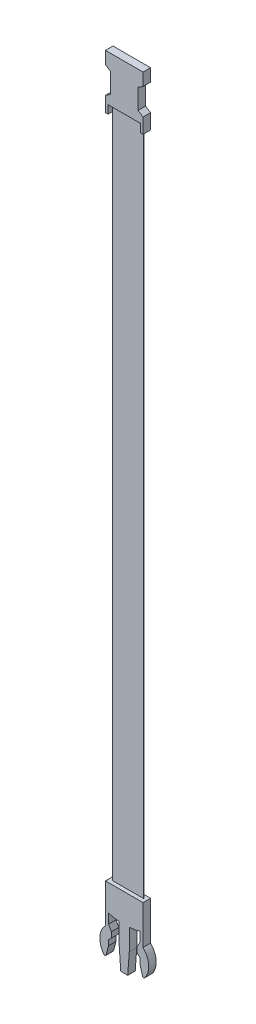
SolidWorks part; units mm, degrees
ref_plane "Plan de face" through (0, 0, 0) normal (0, 0, 1) x (1, 0, 0)
ref_plane "Plan de dessus" through (0, 0, 0) normal (0, 1, 0) x (1, 0, 0)
ref_plane "Plan de droite" through (0, 0, 0) normal (1, 0, 0) x (0, 0, -1)
sketch "Esquisse1" plane through (0, 0, 0) normal (0, 0, 1) x (1, 0, 0)
  line L1 (0, 0) -> (25, 0)
  line L2 (0, 0) -> (0, 550)
  line L3 (0, 550) -> (25, 550)
  line L4 (25, 0) -> (25, 550)
  dimension "D1" = 25
  dimension "D2" = 550
extrude "Extrusion1" add sketch "Esquisse1" along normal blind 0.2
sketch "Esquisse2" plane through (0, 0, 0.2) normal (0, 0, 1) x (1, 0, 0)
  line L0 (-2.5, 545.8754) -> (-2.5, 557.8754)
  line L1 (25, 550) -> (0, 550) construction
  line L2 (12.5, 550) -> (12.5, 576.3626) construction
  line L3 (-0.4001, 545.8754) -> (-0.4001, 552.4561)
  line L4 (-0.4001, 545.8754) -> (-2.5, 545.8754)
  line L5 (1.5, 576.4047) -> (1.5, 560.4047)
  line L6 (-2.5, 557.8754) -> (1.5, 560.4047)
  line L7 (27.5, 578.9341) -> (27.5, 588.9341)
  line L8 (-2.5, 578.9341) -> (1.5, 576.4047)
  line L9 (-2.5, 578.9341) -> (-2.5, 588.9341)
  line L10 (-2.5, 588.9341) -> (27.5, 588.9341)
  line L11 (-0.4001, 552.4561) -> (25.4001, 552.4561)
  line L12 (27.5, 578.9341) -> (23.5, 576.4047)
  line L13 (27.5, 557.8754) -> (23.5, 560.4047)
  line L14 (23.5, 576.4047) -> (23.5, 560.4047)
  line L15 (25.4001, 545.8754) -> (27.5, 545.8754)
  line L16 (25.4001, 545.8754) -> (25.4001, 552.4561)
  line L17 (27.5, 545.8754) -> (27.5, 557.8754)
  point P2 (12.5, 550)
  point P9 (12.5, 552.4561)
  point P13 (12.5, 588.9341)
  dimension "D1" = 15
  dimension "D2" = 11
extrude "Extrusion2" add sketch "Esquisse2" along normal blind 3 and the other way blind 3
sketch "Esquisse3" plane through (0, 0, 0.2) normal (0, 0, 1) x (1, 0, 0)
  line L0 (12.5, 0) -> (12.5, -25.1606) construction
  line L1 (-2.5, 15) -> (-2.5, -16.0505)
  line L2 (0, -5.9495) -> (0, -13.6431)
  line L3 (-2.5, 15) -> (27.5, 15)
  line L4 (0, 0) -> (25, 0) construction
  line L5 (0, -13.6431) -> (2.232, -17.8488)
  line L6 (2.232, -17.8488) -> (2.232, -22.1747)
  line L7 (2.232, -22.1747) -> (0, -24.4067)
  line L8 (0, -24.4067) -> (0, -28.5434)
  line L9 (0, -28.5434) -> (-2.0163, -36.0229)
  line L10 (25, -28.5434) -> (27.0163, -36.0229)
  line L11 (25, -24.4067) -> (25, -28.5434)
  line L12 (22.768, -22.1747) -> (25, -24.4067)
  line L13 (22.768, -17.8488) -> (22.768, -22.1747)
  line L14 (25, -13.6431) -> (22.768, -17.8488)
  line L15 (25, -5.9495) -> (25, -13.6431)
  line L16 (27.5, 15) -> (27.5, -16.0505)
  line L17 (8.5, -7.4942) -> (8.5, -24.4535)
  line L18 (16.5, -7.4942) -> (16.5, -24.4535)
  line L19 (9.7308, -41.4128) -> (15.2692, -41.4128)
  line L20 (9.7308, -41.4128) -> (8.5, -24.4535)
  line L21 (15.2692, -41.4128) -> (16.5, -24.4535)
  arc A0 (0, -5.9495) -> (8.5, -7.4942) centre (9.7308, 23.4374) ccw
  arc A1 (-3.7715, -36.376) -> (-2.5, -16.0505) centre (8.3834, -26.9339) cw
  arc A2 (-2.0163, -36.0229) -> (-3.7715, -36.376) centre (-2.9818, -35.7626) cw
  arc A3 (27.0163, -36.0229) -> (28.7715, -36.376) centre (27.9818, -35.7626) ccw
  arc A4 (28.7715, -36.376) -> (27.5, -16.0505) centre (16.6166, -26.9339) ccw
  arc A5 (25, -5.9495) -> (16.5, -7.4942) centre (15.2692, 23.4374) cw
  point P32 (12.5, 15)
  dimension "D2" = 1
  dimension "D1" = 15
  dimension "D3" = 15
  dimension "D4" = 4
extrude "Extrusion3" add sketch "Esquisse3" along normal blind 3 and the other way blind 3
